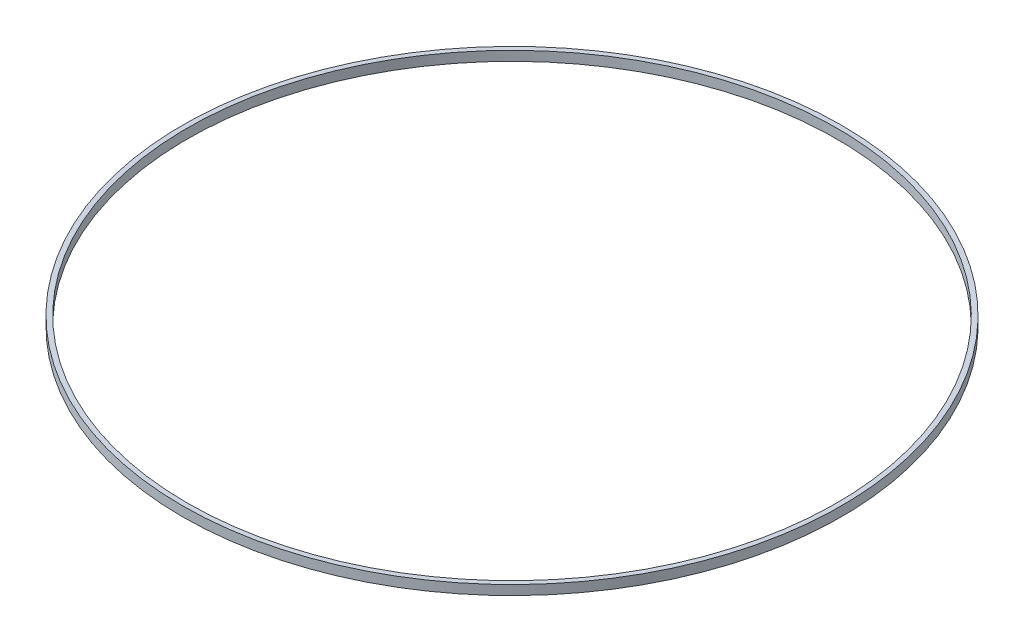
SolidWorks part; units mm, degrees
ref_plane "Front Plane" through (0, 0, 0) normal (0, 0, 1) x (1, 0, 0)
ref_plane "Top Plane" through (0, 0, 0) normal (0, 1, 0) x (1, 0, 0)
ref_plane "Right Plane" through (0, 0, 0) normal (1, 0, 0) x (0, 0, -1)
sketch "Sketch1" plane through (0, 0, 0) normal (0, 1, 0) x (1, 0, 0)
  circle A0 centre (0, 0) radius 345
  circle A1 centre (0, 0) radius 340
extrude "Boss-Extrude1" add sketch "Sketch1" along normal blind 10
